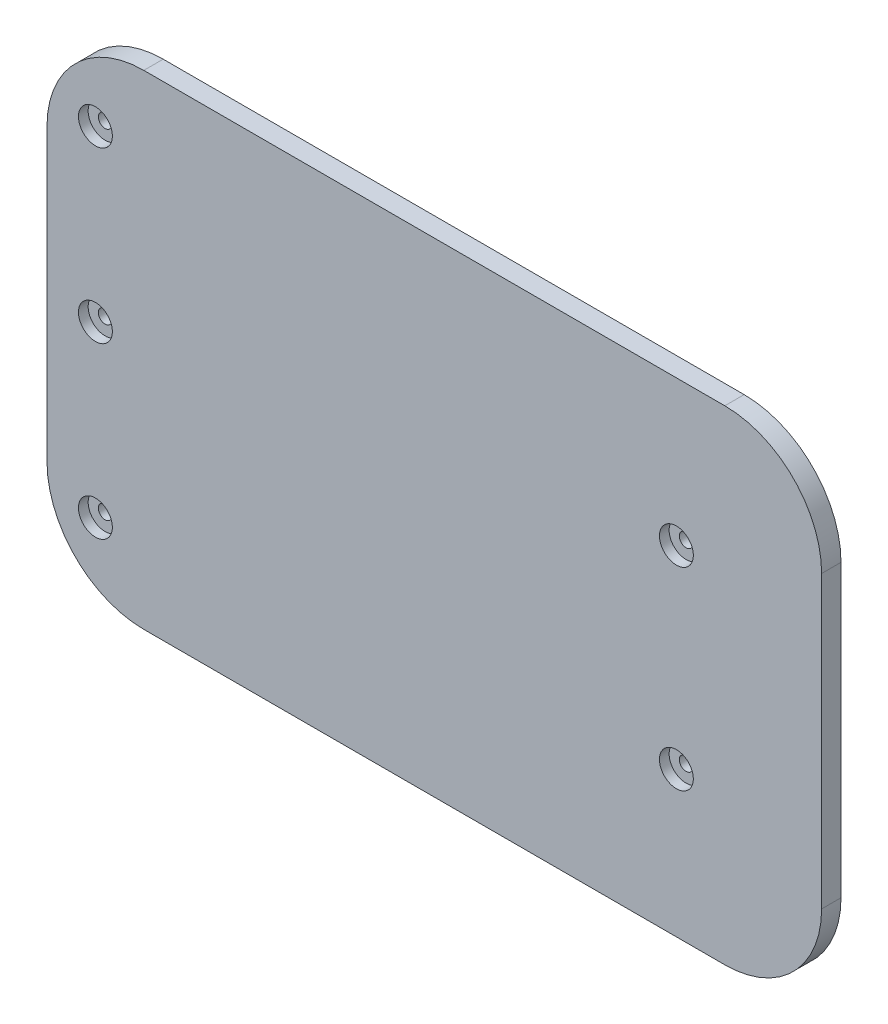
SolidWorks part; units mm, degrees
ref_plane "Front Plane" through (0, 0, 0) normal (0, 0, 1) x (1, 0, 0)
ref_plane "Top Plane" through (0, 0, 0) normal (0, 1, 0) x (1, 0, 0)
ref_plane "Right Plane" through (0, 0, 0) normal (1, 0, 0) x (0, 0, -1)
sketch "Sketch1" plane through (0, 0, 0) normal (0, 0, 1) x (1, 0, 0)
  line L1 (0, 0) -> (160, 0)
  line L2 (0, 0) -> (0, 100)
  line L3 (0, 100) -> (160, 100)
  line L4 (160, 0) -> (160, 100)
  dimension "D1" = 160
  dimension "D2" = 100
extrude "Boss-Extrude1" add sketch "Sketch1" along normal blind 4
fillet "Fillet1" radius 20 4 edges at (0, 0, 2) (160, 0, 2) (160, 100, 2) (0, 100, 2)
sketch "Sketch2" plane through (0, 0, 4) normal (0, 0, 1) x (1, 0, 0)
  line L0 (130, 0) -> (130, 100) construction
  line L1 (140, 100) -> (20, 100) construction
  line L2 (20, 0) -> (140, 0) construction
  line L3 (10, 0) -> (10, 100) construction
  line L4 (160, 20) -> (160, 80) construction
  line L5 (0, 80) -> (0, 20) construction
  circle A0 centre (130, 30) radius 1.4
  circle A1 centre (130, 70) radius 1.4
  circle A2 centre (10, 15) radius 1.4
  circle A3 centre (10, 50) radius 1.4
  circle A4 centre (10, 85) radius 1.4
  dimension "D5" = 2.8
  dimension "D6" = 2.8
  dimension "D7" = 2.8
  dimension "D10" = 2.8
  dimension "D11" = 2.8
  dimension "D1" = 30
  dimension "D2" = 10
  dimension "D3" = 15
  dimension "D4" = 15
  dimension "D8" = 30
  dimension "D9" = 30
extrude "Cut-Extrude1" cut sketch "Sketch2" against normal blind 4
sketch "Sketch3" plane through (0, 0, 4) normal (0, 0, 1) x (1, 0, 0)
  circle A0 centre (130, 30) radius 3.5
  circle A1 centre (130, 70) radius 3.5
  circle A2 centre (10, 85) radius 3.5
  circle A3 centre (10, 50) radius 3.5
  circle A4 centre (10, 15) radius 3.5
  dimension "D1" = 7
  dimension "D2" = 7
  dimension "D3" = 7
  dimension "D4" = 7
  dimension "D5" = 7
extrude "Cut-Extrude2" cut sketch "Sketch3" against normal blind 2
